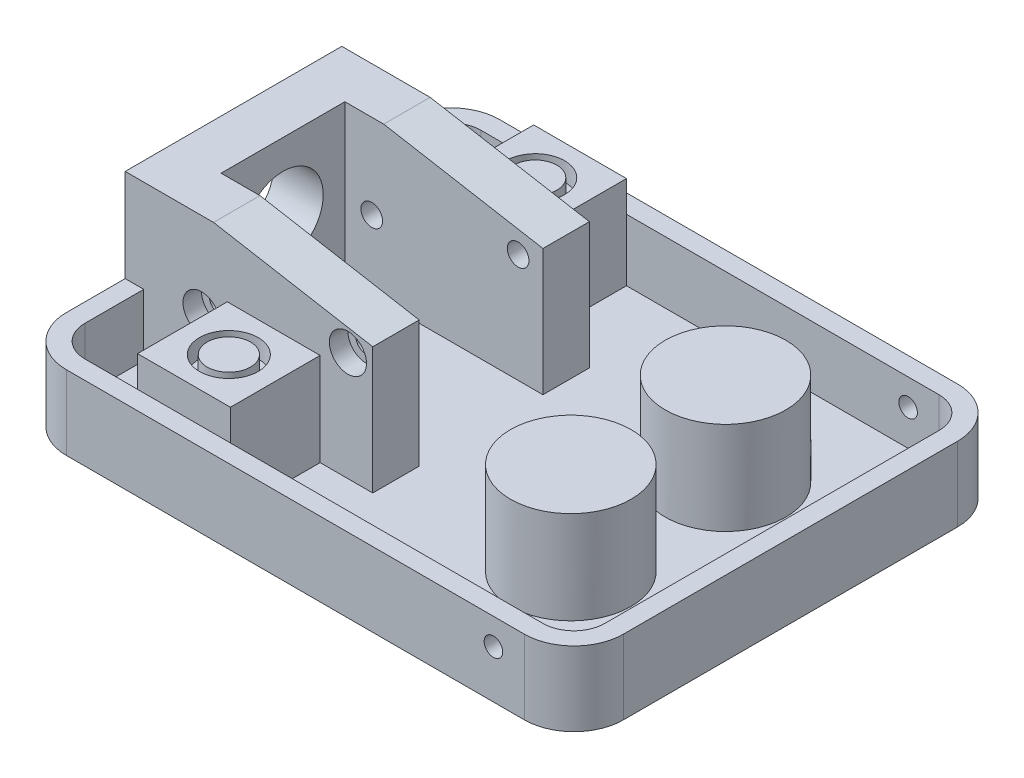
SolidWorks part; units mm, degrees
ref_plane "Front Plane" through (0, 0, 0) normal (0, 0, 1) x (1, 0, 0)
ref_plane "Top Plane" through (0, 0, 0) normal (0, 1, 0) x (1, 0, 0)
ref_plane "Right Plane" through (0, 0, 0) normal (1, 0, 0) x (0, 0, -1)
sketch "Sketch1" plane through (0, 0, 0) normal (0, 1, 0) x (1, 0, 0)
  line L0 (40, 7.5) -> (8, 7.5)
  line L1 (0, 0) -> (40, 0)
  line L2 (0, 0) -> (0, 35)
  line L3 (0, 35) -> (40, 35)
  line L4 (40, 0) -> (40, 7.5)
  line L9 (8, 7.5) -> (8, 27.5)
  line L10 (8, 27.5) -> (40, 27.5)
  line L11 (40, 27.5) -> (40, 35)
  dimension "D1" = 40
  dimension "D2" = 35
  dimension "D3" = 20
  dimension "D4" = 8
extrude "Boss-Extrude1" add sketch "Sketch1" along normal blind 25
sketch "Sketch2" plane through (0, 0, 0) normal (0, 0, 1) x (1, 0, 0)
  line L0 (35.9885, 17.6177) -> (34.1999, 7.4742)
  line L1 (34.1999, 7.4742) -> (12.3372, 11.3292)
  line L2 (8, 25) -> (8, 0) construction
  line L3 (8, 25) -> (8, 0)
  line L4 (0, 0) -> (40, 0)
  line L5 (40, 0) -> (40, 25)
  line L6 (40, 25) -> (0, 25)
  line L7 (0, 25) -> (0, 0)
  line L8 (0, 0) -> (40, 0)
  line L9 (40, 0) -> (40, 25)
  line L10 (40, 25) -> (0, 25)
  line L11 (0, 25) -> (0, 0)
  line L12 (12.7062, 23.5) -> (36.2924, 19.3411)
  line L13 (10.6138, 11.6331) -> (12.7062, 23.5)
  line L14 (14.2772, 25) -> (40, 20.4644)
  circle A0 centre (12.3372, 11.3292) radius 1.75
  circle A1 centre (35.9885, 17.6177) radius 1.75
  dimension "D4" = 3.5
  dimension "D2" = 22.2
  dimension "D3" = 10.3
  dimension "D5" = 10
  dimension "D6" = 1.5
  dimension "D7" = 10
  dimension "D8" = 1.75
  dimension "D1" = 0
extrude "Cut-Extrude1" cut sketch "Sketch2" against normal up to surface (35 mm away)
sketch "Sketch3" plane through (0, 0, 0) normal (0, -1, 0) x (1, 0, 0)
  line L0 (87, 9.5) -> (87, -44.5)
  line L1 (82, 17.5) -> (8, 17.5)
  line L2 (90, 9.5) -> (90, -44.5)
  line L3 (82, -52.5) -> (8, -52.5)
  line L4 (0, 9.5) -> (0, -44.5)
  line L5 (82, 14.5) -> (8, 14.5)
  line L6 (3, 9.5) -> (3, -44.5)
  line L7 (82, -49.5) -> (8, -49.5)
  line L12 (0, 0) -> (0, -35)
  line L13 (0, -35) -> (40, -35)
  line L14 (40, -35) -> (40, -27.5)
  line L15 (40, -27.5) -> (8, -27.5)
  line L16 (8, -27.5) -> (8, -7.5)
  line L17 (8, -7.5) -> (40, -7.5)
  line L18 (40, -7.5) -> (40, 0)
  line L19 (40, 0) -> (0, 0)
  line L20 (0, 0) -> (0, -35)
  line L21 (0, -35) -> (40, -35)
  line L22 (40, -35) -> (40, -27.5)
  line L23 (40, -27.5) -> (8, -27.5)
  line L24 (8, -27.5) -> (8, -7.5)
  line L25 (8, -7.5) -> (40, -7.5)
  line L26 (40, -7.5) -> (40, 0)
  line L27 (40, 0) -> (0, 0)
  arc A0 (0, 9.5) -> (8, 17.5) centre (8, 9.5) cw
  arc A1 (0, -44.5) -> (8, -52.5) centre (8, -44.5) ccw
  arc A2 (82, -52.5) -> (90, -44.5) centre (82, -44.5) ccw
  arc A3 (90, 9.5) -> (82, 17.5) centre (82, 9.5) ccw
  arc A4 (82, -49.5) -> (87, -44.5) centre (82, -44.5) ccw
  arc A5 (87, 9.5) -> (82, 14.5) centre (82, 9.5) ccw
  arc A6 (3, 9.5) -> (8, 14.5) centre (8, 9.5) cw
  arc A7 (3, -44.5) -> (8, -49.5) centre (8, -44.5) ccw
  point P14 (0, -17.5)
  point P16 (0, -17.5)
  line M2 (0, -35) -> (40, -35)
  line M8 (40, 0) -> (0, 0)
  dimension "D1" = 8
  dimension "D2" = 90
  dimension "D3" = 70
  dimension "D4" = 0
  dimension "D5" = 3
extrude "Boss-Extrude2" add sketch "Sketch3" against normal blind 10 contours A7 L6 L4 A1 L3 A2 L2 A3 L1 A0 A6 L5 A5 L0 A4 L7 M2 M8
sketch "Sketch4" plane through (0, 0, 0) normal (0, -1, 0) x (1, 0, 0)
  line L0 (82, -52.5) -> (8, -52.5) construction
  line L1 (0, -44.5) -> (0, 9.5) construction
  line L2 (90, 9.5) -> (90, -44.5) construction
  line L3 (82, 17.5) -> (8, 17.5) construction
  line L4 (82, -52.5) -> (8, -52.5)
  line L5 (0, -44.5) -> (0, 9.5)
  line L6 (90, 9.5) -> (90, -44.5)
  line L7 (82, 17.5) -> (8, 17.5)
  arc A0 (82, -52.5) -> (90, -44.5) centre (82, -44.5) ccw construction
  arc A1 (0, -44.5) -> (8, -52.5) centre (8, -44.5) ccw construction
  arc A2 (8, 17.5) -> (0, 9.5) centre (8, 9.5) ccw construction
  arc A3 (90, 9.5) -> (82, 17.5) centre (82, 9.5) ccw construction
  arc A4 (82, -52.5) -> (90, -44.5) centre (82, -44.5) ccw
  arc A5 (0, -44.5) -> (8, -52.5) centre (8, -44.5) ccw
  arc A6 (8, 17.5) -> (0, 9.5) centre (8, 9.5) ccw
  arc A7 (90, 9.5) -> (82, 17.5) centre (82, 9.5) ccw
extrude "Boss-Extrude3" add sketch "Sketch4" along normal blind 2
sketch "Sketch5" plane through (0, 0, 17.5) normal (0, 0, 1) x (1, 0, 0)
  line L1 (90, 10) -> (90, -2) construction
  line L2 (90, 10) -> (90, -2)
  line L4 (8, 10) -> (8, -2)
  line L5 (8, -2) -> (82, -2)
  line L6 (82, -2) -> (82, 10)
  line L7 (82, 10) -> (8, 10)
  line L8 (8, 10) -> (8, -2)
  line L9 (8, -2) -> (82, -2)
  line L10 (82, -2) -> (82, 10)
  line L20 (82, 10) -> (8, 10)
  circle A0 centre (77, 5.7472) radius 1.5
  dimension "D3" = 3
  dimension "D2" = 13
  dimension "D1" = 0
extrude "Cut-Extrude2" cut sketch "Sketch5" against normal through all contours A0
sketch "Sketch6" plane through (0, 0, 0) normal (0, 0, 1) x (1, 0, 0)
  circle A0 centre (12.3372, 11.3292) radius 3
  circle A1 centre (35.9885, 17.6177) radius 3
  circle M1 centre (35.9885, 17.6177) radius 1.75
  circle M2 centre (12.3372, 11.3292) radius 1.75
  dimension "D1" = 6
extrude "Cut-Extrude3" cut sketch "Sketch6" against normal blind 3 contours A0 M2 | A1 M1
sketch "Sketch7" plane through (0, 0, -35) normal (0, 0, -1) x (-1, 0, 0)
  line L0 (-40, 0) -> (-3, 0) construction
  line L1 (-32.8131, 17.6177) -> (-34.4008, 20.3677)
  line L2 (-34.4008, 20.3677) -> (-37.5762, 20.3677)
  line L3 (-37.5762, 20.3677) -> (-39.1639, 17.6177)
  line L4 (-39.1639, 17.6177) -> (-37.5762, 14.8677)
  line L5 (-37.5762, 14.8677) -> (-34.4008, 14.8677)
  line L6 (-34.4008, 14.8677) -> (-32.8131, 17.6177)
  line L7 (-9.1618, 11.3292) -> (-10.7495, 14.0792)
  line L8 (-10.7495, 14.0792) -> (-13.9249, 14.0792)
  line L9 (-13.9249, 14.0792) -> (-15.5126, 11.3292)
  line L10 (-15.5126, 11.3292) -> (-13.9249, 8.5792)
  line L11 (-13.9249, 8.5792) -> (-10.7495, 8.5792)
  line L12 (-10.7495, 8.5792) -> (-9.1618, 11.3292)
  line L13 (-40, 0) -> (-3, 0)
  circle A0 centre (-35.9885, 17.6177) radius 2.75 construction
  circle A1 centre (-12.3372, 11.3292) radius 2.75 construction
  circle M6 centre (-35.9885, 17.6177) radius 1.75
  circle M7 centre (-12.3372, 11.3292) radius 1.75
  dimension "D1" = 5.5
  dimension "D2" = 5.5
extrude "Cut-Extrude4" cut sketch "Sketch7" against normal blind 3 contours L5 L6 L1 L2 L3 L4 M6 | L11 L12 L7 L8 L9 L10 M7
sketch "Sketch8" plane through (0, 0, 0) normal (0, 1, 0) x (1, 0, 0)
  line L0 (16.5, 35) -> (16.5, 49.5)
  line L1 (31.5, 35) -> (31.5, 49.5)
  line L2 (16.5, 0) -> (16.5, -14.5)
  line L3 (31.5, -14.5) -> (31.5, 0)
  line L12 (40, 0) -> (3, 0)
  line L13 (3, 0) -> (3, -9.5)
  line L14 (8, -14.5) -> (82, -14.5)
  line L15 (87, -9.5) -> (87, 44.5)
  line L16 (82, 49.5) -> (8, 49.5)
  line L17 (3, 44.5) -> (3, 35)
  line L18 (3, 35) -> (40, 35)
  line L19 (40, 35) -> (40, 27.5)
  line L20 (40, 27.5) -> (8, 27.5)
  line L21 (8, 27.5) -> (8, 7.5)
  line L22 (8, 7.5) -> (40, 7.5)
  line L23 (40, 7.5) -> (40, 0)
  line L24 (40, 0) -> (3, 0)
  line L25 (3, 0) -> (3, -9.5)
  line L26 (8, -14.5) -> (82, -14.5)
  line L27 (87, -9.5) -> (87, 44.5)
  line L28 (82, 49.5) -> (8, 49.5)
  line L29 (3, 44.5) -> (3, 35)
  line L30 (3, 35) -> (40, 35)
  line L31 (40, 35) -> (40, 27.5)
  line L32 (40, 27.5) -> (8, 27.5)
  line L33 (8, 27.5) -> (8, 7.5)
  line L34 (8, 7.5) -> (40, 7.5)
  line L35 (40, 7.5) -> (40, 0)
  arc A4 (3, -9.5) -> (8, -14.5) centre (8, -9.5) ccw
  arc A5 (82, -14.5) -> (87, -9.5) centre (82, -9.5) ccw
  arc A6 (87, 44.5) -> (82, 49.5) centre (82, 44.5) ccw
  arc A7 (8, 49.5) -> (3, 44.5) centre (8, 44.5) ccw
  arc A8 (3, -9.5) -> (8, -14.5) centre (8, -9.5) ccw
  arc A9 (82, -14.5) -> (87, -9.5) centre (82, -9.5) ccw
  arc A10 (87, 44.5) -> (82, 49.5) centre (82, 44.5) ccw
  arc A11 (8, 49.5) -> (3, 44.5) centre (8, 44.5) ccw
  point P22 (21.5, 35)
  line M21 (40, 0) -> (3, 0)
  line M24 (8, -14.5) -> (82, -14.5)
  line M28 (82, 49.5) -> (8, 49.5)
  line M31 (3, 35) -> (40, 35)
  dimension "D2" = 15
  dimension "D3" = 10
  dimension "D1" = 0
extrude "Boss-Extrude4" add sketch "Sketch8" along normal blind 15 contours L3 L2 M24 M21 | L1 L0 M31 M28
sketch "Sketch9" plane through (0, 15, 0) normal (0, 1, 0) x (1, 0, 0)
  line L4 (16.5, -14.5) -> (31.5, -14.5)
  line L5 (31.5, -14.5) -> (31.5, 0)
  line L6 (31.5, 0) -> (16.5, 0)
  line L7 (16.5, 0) -> (16.5, -14.5)
  line L8 (16.5, -14.5) -> (31.5, -14.5)
  line L9 (31.5, -14.5) -> (31.5, 0)
  line L10 (31.5, 0) -> (16.5, 0)
  line L11 (16.5, 0) -> (16.5, -14.5)
  line L12 (16.5, 35) -> (31.5, 35)
  line L13 (31.5, 35) -> (31.5, 49.5)
  line L14 (31.5, 49.5) -> (16.5, 49.5)
  line L15 (16.5, 49.5) -> (16.5, 35)
  line L16 (16.5, 49.5) -> (31.5, 49.5)
  line L18 (31.5, -14.5) -> (16.5, -14.5)
  line L19 (31.5, -14.5) -> (16.5, -14.5)
  line L20 (8, 49.5) -> (16.5, 49.5)
  line L21 (16.5, 35) -> (31.5, 35)
  line L22 (0, 35) -> (3, 35)
  line L23 (31.5, 35) -> (31.5, 49.5)
  line L24 (31.5, 49.5) -> (82, 49.5)
  line L25 (87, 44.5) -> (87, -9.5)
  line L26 (82, -14.5) -> (31.5, -14.5)
  line L27 (31.5, 49.5) -> (16.5, 49.5)
  line L28 (3, 0) -> (0, 0)
  line L29 (16.5, 49.5) -> (16.5, 35)
  line L30 (16.5, -14.5) -> (8, -14.5)
  line L31 (3, -9.5) -> (3, 0)
  line L33 (0, 0) -> (0, -9.5)
  line L34 (8, -17.5) -> (82, -17.5)
  line L35 (90, -9.5) -> (90, 44.5)
  line L36 (82, 52.5) -> (8, 52.5)
  line L37 (0, 44.5) -> (0, 35)
  line L39 (3, 35) -> (3, 44.5)
  circle A0 centre (24, -7.25) radius 4.75
  circle A1 centre (24, -7.25) radius 3.5
  circle A2 centre (24, 42.25) radius 4.75
  circle A3 centre (24, 42.25) radius 3.5
  arc A8 (8, 49.5) -> (3, 44.5) centre (8, 44.5) ccw
  arc A9 (87, 44.5) -> (82, 49.5) centre (82, 44.5) ccw
  arc A10 (82, -14.5) -> (87, -9.5) centre (82, -9.5) ccw
  arc A11 (3, -9.5) -> (8, -14.5) centre (8, -9.5) ccw
  arc A12 (0, -9.5) -> (8, -17.5) centre (8, -9.5) ccw
  arc A13 (82, -17.5) -> (90, -9.5) centre (82, -9.5) ccw
  arc A14 (90, 44.5) -> (82, 52.5) centre (82, 44.5) ccw
  arc A15 (8, 52.5) -> (0, 44.5) centre (8, 44.5) ccw
  point P36 (16.5, -7.25)
  point P41 (16.5, 42.25)
  point P45 (24, -14.5)
  dimension "D2" = 7
  dimension "D3" = 9.5
  dimension "D1" = 0
  dimension "D4" = 0
  dimension "D5" = 0
extrude "Cut-Extrude5" cut sketch "Sketch9" against normal blind 3 contours A2 A3 | A0 A1
sketch "Sketch11" plane through (0, 0, 0) normal (0, 1, 0) x (1, 0, 0)
  line L1 (87, -9.5) -> (87, 44.5) construction
  line L3 (87, -9.5) -> (87, 44.5)
  line L4 (82, 49.5) -> (31.5, 49.5) construction
  circle A0 centre (67, 30) radius 9.75
  circle A1 centre (67, 5) radius 9.75
  dimension "D1" = 19.5
  dimension "D3" = 25
  dimension "D2" = 20
  dimension "D4" = 19.5
extrude "Boss-Extrude5" add sketch "Sketch11" along normal blind 15 contours A0 | A1
sketch "Sketch12" plane through (0, 0, 0) normal (-1, 0, 0) x (0, 0, 1)
  line L0 (-7.5, 0) -> (-27.5, 0) construction
  line L1 (-7.5, 0) -> (-27.5, 0)
  line L2 (-20, 2.5) -> (-20, 25)
  line L3 (-15, 2.5) -> (-15, 25)
  line L8 (-44.5, 10) -> (-44.5, -2)
  line L9 (-44.5, -2) -> (9.5, -2)
  line L10 (9.5, -2) -> (9.5, 10)
  line L11 (9.5, 10) -> (0, 10)
  line L12 (0, 10) -> (0, 25)
  line L13 (0, 25) -> (-35, 25)
  line L14 (-35, 25) -> (-35, 10)
  line L15 (-35, 10) -> (-44.5, 10)
  line L16 (-44.5, 10) -> (-44.5, -2)
  line L17 (-44.5, -2) -> (9.5, -2)
  line L18 (9.5, -2) -> (9.5, 10)
  line L19 (9.5, 10) -> (0, 10)
  line L20 (0, 10) -> (0, 25)
  line L21 (0, 25) -> (-35, 25)
  line L22 (-35, 25) -> (-35, 10)
  line L23 (-35, 10) -> (-44.5, 10)
  arc A0 (-20, 2.5) -> (-15, 2.5) centre (-17.5, 2.5) ccw
  circle A1 centre (-17.5, 13.7592) radius 6.5
  point P12 (-17.5, 0)
  line M17 (0, 25) -> (-35, 25)
  dimension "D3" = 13
  dimension "D2" = 5
  dimension "D1" = 0
extrude "Cut-Extrude6" cut sketch "Sketch12" against normal up to next contours L2 A0 L3 M17 | L3 A1 | L3 A1 L2 | L2 A1
equation "\"D2@Sketch7\"=\"D1@Sketch7\""
